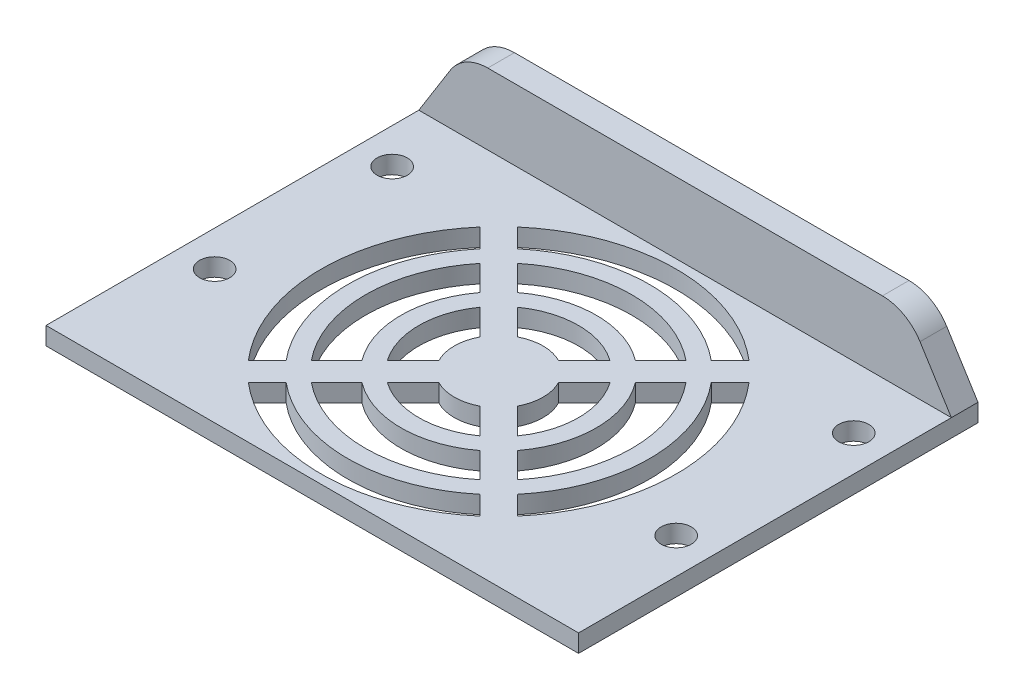
SolidWorks part; units mm, degrees
material "ABS PC"
ref_plane "Front Plane" through (0, 0, 0) normal (0, 0, 1) x (1, 0, 0)
ref_plane "Top Plane" through (0, 0, 0) normal (0, 1, 0) x (1, 0, 0)
ref_plane "Right Plane" through (0, 0, 0) normal (1, 0, 0) x (0, 0, -1)
sketch "Sketch1" plane through (0, 0, 0) normal (0, 1, 0) x (1, 0, 0)
  line L0 (0, 0) -> (0, 45)
  line L1 (0, 0) -> (60, 0)
  line L2 (0, 45) -> (60, 45)
  line L3 (60, 0) -> (60, 45)
  dimension "D1" = 60
  dimension "D2" = 45
extrude "Boss-Extrude1" add sketch "Sketch1" along normal blind 2
hole_wizard "Ø3.4 (3.4) Diameter Hole1" positions "Sketch3" profile "Sketch2" hole size "Ø3.4" standard "ANSI Metric" end condition through all
sketch "Sketch3" plane through (0, 2, 0) normal (0, 1, 0) x (1, 0, 0)
  line L0 (0, 0) -> (60, 0) construction
  line L6 (0, 45) -> (0, 0) construction
  line L7 (60, 0) -> (60, 45) construction
  point P0 (4, 15)
  point P2 (4, 35)
  point P4 (56, 35)
  point P6 (56, 15)
  dimension "D1" = 15
  dimension "D2" = 20
  dimension "D3" = 4
  dimension "D4" = 4
sketch "Sketch2" plane through (4, 2, -15) normal (1, 0, 0) x (0, 0, 1)
  line L0 (0, 0) -> (0, 2)
  line L1 (0, 2) -> (1.7, 2)
  line L2 (1.7, 2) -> (1.7, 0)
  line L5 (1.7, 0) -> (0, 0)
  line L11 (0, -6.35) -> (0, 107.95) construction
  dimension "Thru Hole Dia." = 3.4
  dimension "Thru Hole Depth" = 2
sketch "Sketch5" plane through (0, 2, 0) normal (0, 1, 0) x (1, 0, 0)
  line L1 (0, 0) -> (60, 0) construction
  line L2 (60, 45) -> (0, 45) construction
  line L3 (60, 0) -> (60, 45) construction
  line L5 (60, 45) -> (0, 45) construction
  line L6 (20.5072, 32.6141) -> (23.3551, 29.7662)
  line L9 (24.7857, 28.3356) -> (27.688, 25.4333)
  line L11 (32.312, 25.4333) -> (35.2143, 28.3356)
  line L12 (36.6449, 29.7662) -> (39.4928, 32.6141)
  line L13 (40.9133, 34.0346) -> (43.0416, 36.163)
  line L14 (16.9584, 36.163) -> (19.0867, 34.0346)
  circle A0 centre (30, 21) radius 2.5
  arc A1 (27.688, 25.4333) -> (32.312, 25.4333) centre (30, 21) cw
  arc A2 (24.7857, 28.3356) -> (35.2143, 28.3356) centre (30, 21) cw
  arc A3 (36.6449, 29.7662) -> (23.3551, 29.7662) centre (30, 21) ccw
  arc A4 (20.5072, 32.6141) -> (39.4928, 32.6141) centre (30, 21) cw
  arc A5 (19.0867, 34.0346) -> (40.9133, 34.0346) centre (30, 21) cw
  arc A6 (16.9584, 36.163) -> (43.0416, 36.163) centre (30, 21) cw
  point P2 (30, 45)
  point P10 (30, 45)
  point P14 (30, 45)
  dimension "D3" = 30
  dimension "D4" = 5
  dimension "D5" = 9
  dimension "D6" = 11
  dimension "D7" = 15
  dimension "D8" = 17
  dimension "D9" = 20
  dimension "D12" = 5
  dimension "D1" = 13.0416
  dimension "D2" = 21
  dimension "D10" = 13.0416
  dimension "D11" = 10.9133
extrude "Air holes" cut sketch "Sketch5" against normal through all
pattern_circular "CirPattern1" count 4 every 90 about axis through (30, 0, -21) along (0, 1, 0) of "Air holes"
sketch "Sketch6" plane through (0, 2, 0) normal (0, 1, 0) x (1, 0, 0)
  circle A0 centre (30, 21) radius 2.5
extrude "Boss-Extrude3" add sketch "Sketch6" against normal blind 2
sketch "Sketch10" plane through (0, 0, -45) normal (0, 0, -1) x (-1, 0, 0)
  line L0 (-60, 2) -> (-56.4688, 7.65)
  line L1 (-52.2288, 10) -> (-7.7712, 10)
  line L2 (-3.5312, 7.65) -> (0, 2)
  line L3 (0, 2) -> (0, 0)
  line L4 (0, 0) -> (-60, 0)
  line L5 (-60, 0) -> (-60, 2)
  line L6 (-60, 2) -> (0, 2) construction
  arc A0 (-3.5312, 7.65) -> (-7.7712, 10) centre (-7.7712, 5) ccw
  arc A1 (-52.2288, 10) -> (-56.4688, 7.65) centre (-52.2288, 5) ccw
  point P14 (-5, 10)
  point P17 (-55, 10)
  dimension "D4" = 5
  dimension "D1" = 8
  dimension "D2" = 5
  dimension "D3" = 5
extrude "Boss-Extrude5" add sketch "Sketch10" against normal blind 3
